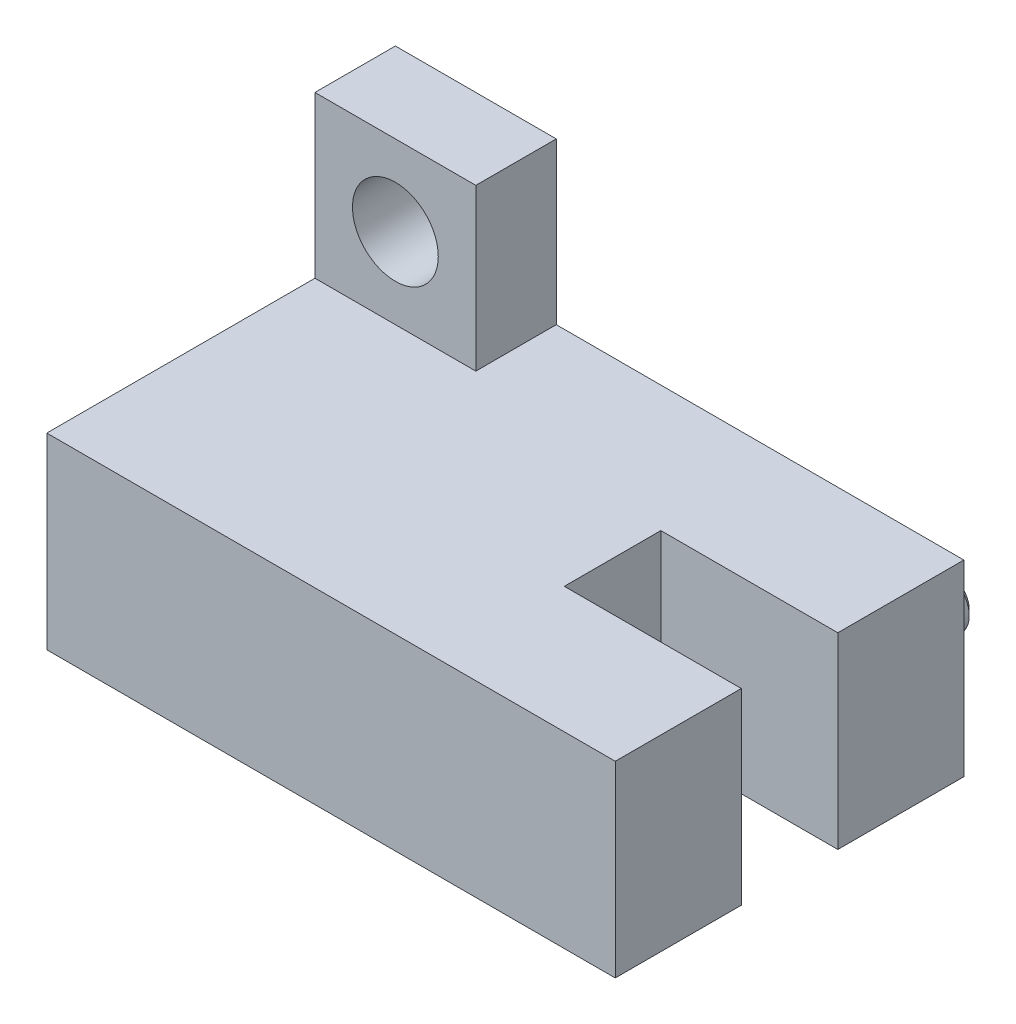
SolidWorks part; units mm, degrees
ref_plane "前视基准面" through (0, 0, 0) normal (0, 0, 1) x (1, 0, 0)
ref_plane "上视基准面" through (0, 0, 0) normal (0, 1, 0) x (1, 0, 0)
ref_plane "右视基准面" through (0, 0, 0) normal (1, 0, 0) x (0, 0, -1)
sketch "草图1" plane through (0, 0, 0) normal (0, 0, 1) x (1, 0, 0)
  line L0 (-3, -0.5) -> (3, -0.5)
  line L1 (-3, 12.5) -> (3, 12.5)
  line L2 (-3, 12.5) -> (-3, -0.5)
  line L3 (0, -1000) -> (0, 49000) construction
  line L4 (3, 12.5) -> (3, -0.5)
  circle A0 centre (0, 9.5) radius 1.6
  dimension "D4" = 3.2
  dimension "D5" = 10
  dimension "D1" = 13
  dimension "D2" = 6
  dimension "D3" = 3
  dimension "D6" = 3
extrude "拉伸1" add sketch "草图1" along normal blind 3
sketch "草图3" plane through (0, 0, 0) normal (0, 0, -1) x (-1, 0, 0)
  line L1 (3, -0.5) -> (-18.2, -0.5)
  line L2 (3, -0.5) -> (3, 6.5)
  line L3 (3, 6.5) -> (-18.2, 6.5)
  line L4 (-18.2, -0.5) -> (-18.2, 6.5)
  dimension "D1" = 7
  dimension "D2" = 21.2
extrude "拉伸3" add sketch "草图3" against normal blind 13
sketch "草图4" plane through (0, 6.5, 0) normal (0, 1, 0) x (-1, 0, 0)
  line L0 (-1018.45, 6.5) -> (48981.55, 6.5) construction
  line L1 (-18.2, 13) -> (-18.2, 0) construction
  line L4 (-22.5378, 8.3) -> (-11.6, 8.3)
  line L5 (-22.5378, 8.3) -> (-22.5378, 4.7)
  line L6 (-22.5378, 4.7) -> (-11.6, 4.7)
  line L7 (-11.6, 8.3) -> (-11.6, 4.7)
  point P5 (-18.2, 6.5)
  dimension "D1" = 3.6
  dimension "D2" = 6.6
  dimension "D3" = 1.8
extrude "切除-拉伸1" cut sketch "草图4" against normal blind 13.2
sketch "草图6" plane through (0, 0, 0) normal (0, 0, -1) x (-1, 0, 0)
  line L0 (0, -990.5) -> (0, 49009.5) construction
  line L1 (-15.6, -992.438) -> (-15.6, 49007.562) construction
  line L2 (-1018.25, 3) -> (48981.75, 3) construction
  line L3 (-18.2, 6.5) -> (-18.2, -0.5) construction
  line L4 (-3, 6.5) -> (3, 6.5) construction
  circle A0 centre (-15.6, 3) radius 1
  point P10 (-18.2, 3)
  dimension "D2" = 2
  dimension "D1" = 15.6
  dimension "D3" = 3.5
extrude "拉伸4" add sketch "草图6" along normal blind 2
chamfer "倒角1" distance 0.2 angle 45 1 edges at (14.6, 3, -2)
